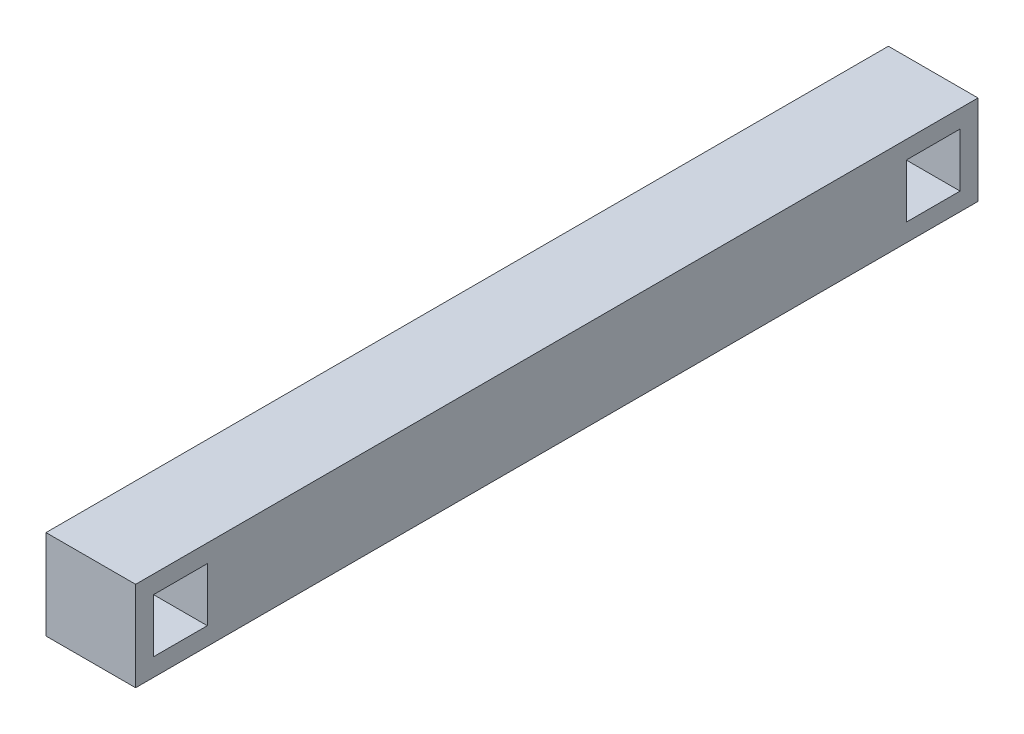
SolidWorks part; units mm, degrees
ref_plane "Front Plane" through (0, 0, 0) normal (0, 0, 1) x (1, 0, 0)
ref_plane "Top Plane" through (0, 0, 0) normal (0, 1, 0) x (1, 0, 0)
ref_plane "Right Plane" through (0, 0, 0) normal (1, 0, 0) x (0, 0, -1)
sketch "Sketch1" plane through (0, 0, 0) normal (0, 0, 1) x (1, 0, 0)
  line L1 (0, 0) -> (5, 0)
  line L2 (0, 0) -> (0, 5)
  line L3 (0, 5) -> (5, 5)
  line L4 (5, 0) -> (5, 5)
  dimension "D1" = 5
  dimension "D2" = 5
extrude "Boss-Extrude1" add sketch "Sketch1" along normal blind 47
sketch "Sketch2" plane through (5, 0, 0) normal (1, 0, 0) x (0, 0, -1)
  line L0 (-47, 0) -> (-47, 5) construction
  line L1 (-46, 1) -> (-43, 1)
  line L2 (-46, 1) -> (-46, 4)
  line L3 (-46, 4) -> (-43, 4)
  line L4 (-43, 1) -> (-43, 4)
  line L5 (-4, 1) -> (-1, 1)
  line L6 (-4, 1) -> (-4, 4)
  line L7 (-4, 4) -> (-1, 4)
  line L8 (-1, 1) -> (-1, 4)
  line L9 (-47, 5) -> (0, 5) construction
  line L10 (0, 0) -> (0, 5) construction
  dimension "D1" = 3
  dimension "D2" = 3
  dimension "D3" = 1
  dimension "D4" = 1
  dimension "D5" = 3
  dimension "D6" = 3
  dimension "D7" = 1
  dimension "D8" = 1
extrude "Cut-Extrude1" cut sketch "Sketch2" against normal blind 47
